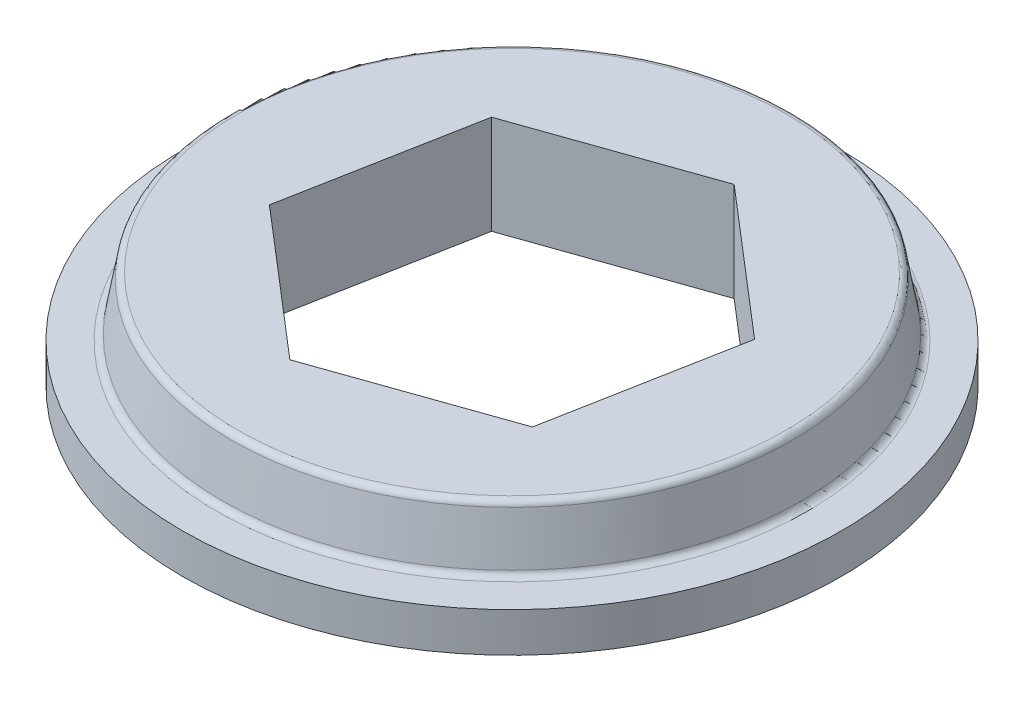
SolidWorks part; units mm, degrees
material "6061-T6 (SS)"
ref_plane "Front Plane" through (0, 0, 0) normal (0, 0, 1) x (1, 0, 0)
ref_plane "Top Plane" through (0, 0, 0) normal (0, 1, 0) x (1, 0, 0)
ref_plane "Right Plane" through (0, 0, 0) normal (1, 0, 0) x (0, 0, -1)
sketch "Sketch1" plane through (0, 0, 0) normal (1, 0, 0) x (0, 0, -1)
  line L0 (0, 8.5249) -> (0, -3.8386) construction
  line L1 (0, 3.81) -> (10.7729, 3.81)
  line L2 (10.7729, 3.81) -> (11.176, 1.524)
  line L3 (11.176, 1.524) -> (12.7, 1.524)
  line L4 (12.7, 1.524) -> (12.7, 0)
  line L5 (12.7, 0) -> (0, 0)
  line L6 (0, 3.81) -> (0, 0)
  dimension "D1" = 2.286
  dimension "D2" = 1.524
  dimension "D3" = 12.7
  dimension "D4" = 100
  dimension "D5" = 11.176
revolve "Revolve1" add sketch "Sketch1" angle 360 about L0
sketch "Sketch2" plane through (0, 3.81, 0) normal (0, 1, 0) x (1, 0, 0)
  line L1 (5.5635, -4.7761) -> (6.918, 2.43)
  line L2 (6.918, 2.43) -> (1.3545, 7.2062)
  line L3 (1.3545, 7.2062) -> (-5.5635, 4.7761)
  line L4 (-5.5635, 4.7761) -> (-6.918, -2.43)
  line L5 (-6.918, -2.43) -> (-1.3545, -7.2062)
  line L6 (-1.3545, -7.2062) -> (5.5635, -4.7761)
  circle A0 centre (0, 0) radius 6.35 construction
  dimension "D1" = 12.7
extrude "Cut-Extrude1" cut sketch "Sketch2" against normal through all
fillet "Fillet1" radius 0.254 2 edges at (0, 3.81, 10.7729) (0, 1.524, 11.176)
